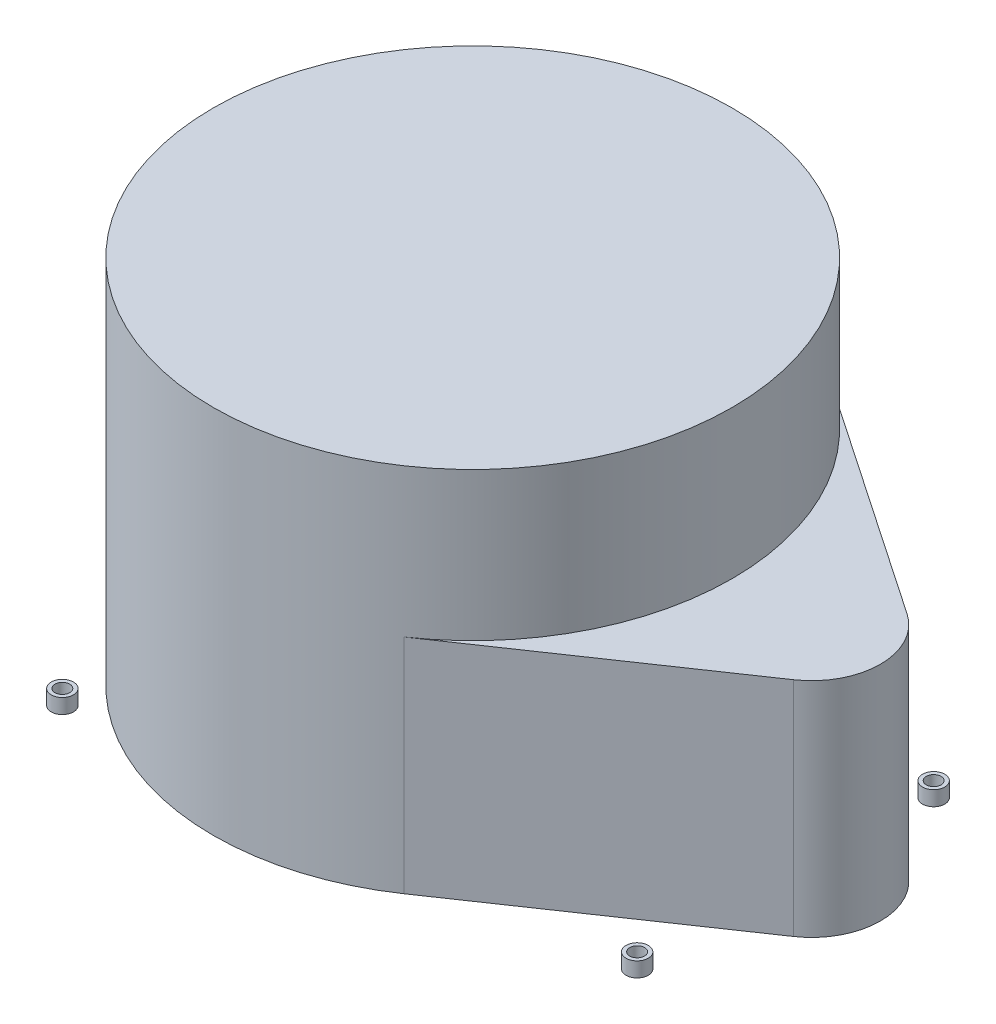
SolidWorks part; units mm, degrees
ref_plane "前视基准面" through (0, 0, 0) normal (0, 0, 1) x (1, 0, 0)
ref_plane "上视基准面" through (0, 0, 0) normal (0, 1, 0) x (1, 0, 0)
ref_plane "右视基准面" through (0, 0, 0) normal (1, 0, 0) x (0, 0, -1)
sketch "草图1" plane through (0, 0, 0) normal (0, 1, 0) x (1, 0, 0)
  line L0 (-35, 0) -> (61, 0) construction
  line L1 (19.6936, 28.9338) -> (50.947, 7.6613)
  line L2 (50.947, -7.6613) -> (19.6936, -28.9338)
  arc A0 (19.6936, 28.9338) -> (19.6936, -28.9338) centre (0, 0) ccw
  arc A3 (50.947, -7.6613) -> (50.947, 7.6613) centre (45.7324, 0) ccw
  point P1 (-35, 0)
  dimension "D1" = 70
  dimension "D2" = 9.2676
  dimension "D3" = 34.241
  dimension "D4" = 34.241
  dimension "D5" = 96
extrude "凸台-拉伸1" add sketch "草图1" along normal blind 30 from offset 5
sketch "草图2" plane through (0, 35, 0) normal (0, 1, 0) x (1, 0, 0)
  circle A0 centre (0, 0) radius 35
extrude "凸台-拉伸2" add sketch "草图2" along normal blind 20
sketch "草图3" plane through (0, 5, 0) normal (0, -1, 0) x (1, 0, 0)
  line L0 (0, 0) -> (53.4925, 0) construction
  circle A0 centre (42.1832, 20) radius 1.5
  circle A2 centre (42.1832, 20) radius 70 construction
  circle A3 centre (-27.3582, 28) radius 1.5
  circle A4 centre (42.1832, -20) radius 1.5
  circle A6 centre (-27.3582, -28) radius 1.5
  circle A7 centre (-27.3582, 28) radius 1
  circle A8 centre (-27.3582, -28) radius 1
  circle A9 centre (42.1832, 20) radius 1
  circle A10 centre (42.1832, -20) radius 1
  dimension "D1" = 3
  dimension "D3" = 140
  dimension "D4" = 3
  dimension "D5" = 56
  dimension "D6" = 2
  dimension "D7" = 2
  dimension "D2" = 20
extrude "凸台-拉伸3" add sketch "草图3" along normal blind 2 separate body contours A0
